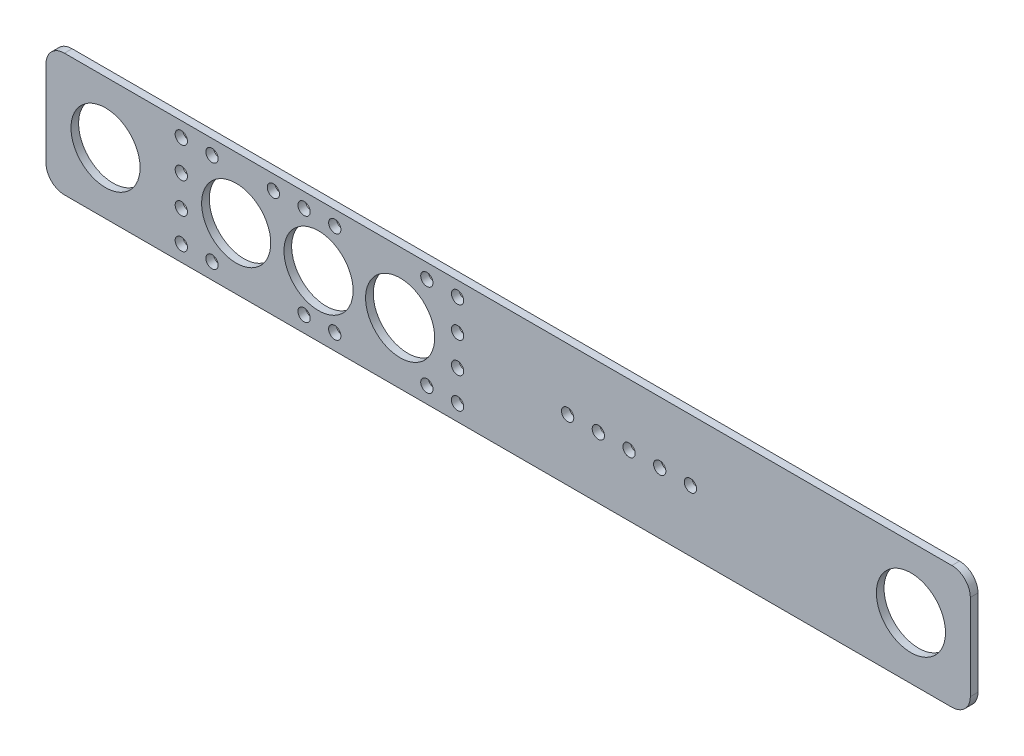
SolidWorks part; units mm, degrees
ref_plane "Front Plane" through (0, 0, 0) normal (0, 0, 1) x (1, 0, 0)
ref_plane "Top Plane" through (0, 0, 0) normal (0, 1, 0) x (1, 0, 0)
ref_plane "Right Plane" through (0, 0, 0) normal (1, 0, 0) x (0, 0, -1)
sketch "Sketch1" plane through (0, 0, 0) normal (0, 0, 1) x (1, 0, 0)
  line L1 (-58.961, 34.7527) -> (323.4919, 34.7527)
  line L2 (-58.961, 34.7527) -> (-58.961, -16.0473)
  line L3 (-58.961, -16.0473) -> (323.4919, -16.0473)
  line L4 (323.4919, 34.7527) -> (323.4919, -16.0473)
  circle A0 centre (-34.3348, 9.3527) radius 14.3002
  circle A1 centre (298.9132, 9.3527) radius 14.3002
  circle A2 centre (53.8032, 9.3527) radius 14.3002
  circle A3 centre (87.5734, 9.3527) radius 14.3002
  circle A4 centre (19.7296, 9.3527) radius 14.3002
  circle A5 centre (98.6198, -9.4307) radius 2.54 construction
  circle A6 centre (111.3198, -9.4307) radius 2.54 construction
  circle A7 centre (111.3198, 3.2693) radius 2.54 construction
  circle A8 centre (111.3198, 15.9693) radius 2.54 construction
  circle A9 centre (111.3198, 28.6693) radius 2.54 construction
  circle A10 centre (98.6198, 28.6693) radius 2.54 construction
  circle A11 centre (47.8198, -9.4307) radius 2.54 construction
  circle A12 centre (60.5198, -9.4307) radius 2.54 construction
  circle A13 centre (47.8198, 28.6693) radius 2.54 construction
  circle A14 centre (60.5198, 28.6693) radius 2.54 construction
  circle A15 centre (35.1198, 28.6693) radius 2.54 construction
  circle A16 centre (9.7198, -9.4307) radius 2.54 construction
  circle A17 centre (-2.9802, -9.4307) radius 2.54 construction
  circle A18 centre (-2.9802, 3.2693) radius 2.54 construction
  circle A19 centre (-2.9802, 15.9693) radius 2.54 construction
  circle A20 centre (9.7198, 28.6693) radius 2.54 construction
  circle A21 centre (-2.9802, 28.6693) radius 2.54 construction
  circle A22 centre (98.6198, -9.4307) radius 2.54
  circle A23 centre (111.3198, -9.4307) radius 2.54
  circle A24 centre (111.3198, 3.2693) radius 2.54
  circle A25 centre (111.3198, 15.9693) radius 2.54
  circle A26 centre (111.3198, 28.6693) radius 2.54
  circle A27 centre (98.6198, 28.6693) radius 2.54
  circle A28 centre (47.8198, -9.4307) radius 2.54
  circle A29 centre (60.5198, -9.4307) radius 2.54
  circle A30 centre (47.8198, 28.6693) radius 2.54
  circle A31 centre (60.5198, 28.6693) radius 2.54
  circle A32 centre (35.1198, 28.6693) radius 2.54
  circle A33 centre (9.7198, -9.4307) radius 2.54
  circle A34 centre (-2.9802, -9.4307) radius 2.54
  circle A35 centre (-2.9802, 3.2693) radius 2.54
  circle A36 centre (-2.9802, 15.9693) radius 2.54
  circle A37 centre (9.7198, 28.6693) radius 2.54
  circle A38 centre (-2.9802, 28.6693) radius 2.54
  circle A39 centre (156.8772, 9.3527) radius 2.54
  circle A40 centre (169.5772, 9.3527) radius 2.54
  circle A41 centre (182.2772, 9.3527) radius 2.54
  circle A42 centre (194.9772, 9.3527) radius 2.54
  circle A43 centre (207.6772, 9.3527) radius 2.54
  dimension "D3" = 25.4
  dimension "D4" = 5
  dimension "D1" = 50.8
  dimension "D2" = 25.4
  dimension "D5" = 88.138
  dimension "D6" = 245.11
extrude "Boss-Extrude1" add sketch "Sketch1" along normal blind 3.175
fillet "Fillet1" radius 7.62 4 edges at (323.4919, 34.7527, 1.5875) (323.4919, -16.0473, 1.5875) (-58.961, -16.0473, 1.5875) (-58.961, 34.7527, 1.5875)
